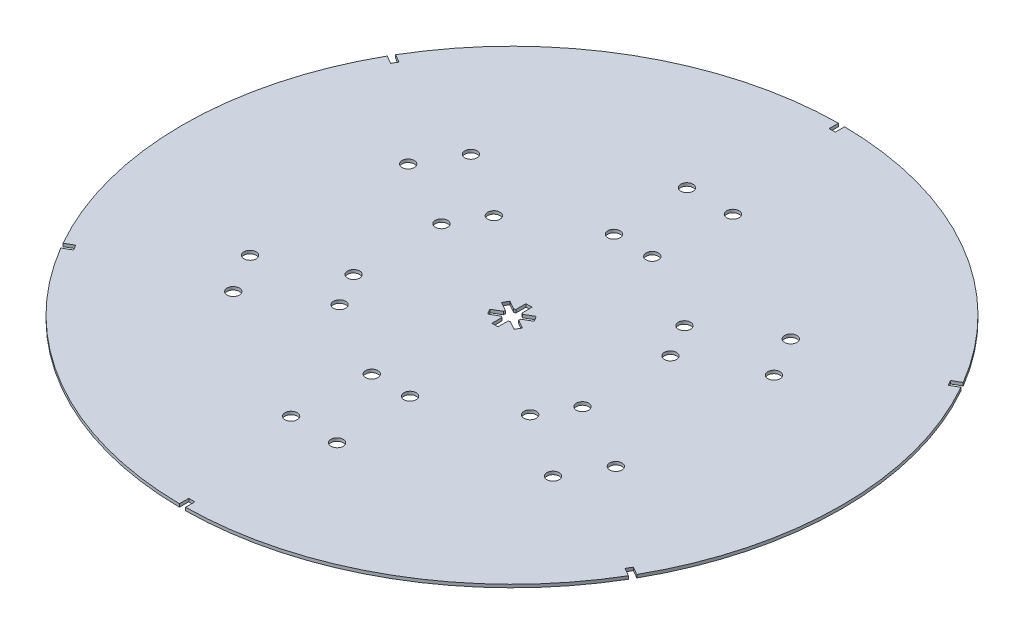
SolidWorks part; units mm, degrees
ref_plane "Front Plane" through (0, 0, 0) normal (0, 0, 1) x (1, 0, 0)
ref_plane "Top Plane" through (0, 0, 0) normal (0, 1, 0) x (1, 0, 0)
ref_plane "Right Plane" through (0, 0, 0) normal (1, 0, 0) x (0, 0, -1)
sketch "Sketch1" plane through (0, 0, 0) normal (0, 1, 0) x (1, 0, 0)
  line L0 (0, -1000) -> (0, 49000) construction
  line L1 (-1000, 0) -> (49000, 0) construction
  line L2 (0, 0) -> (-234.4645, 135.3681) construction
  line L3 (0, 0) -> (234.4645, 135.3681) construction
  line L4 (0, 0) -> (-234.4645, -135.3681) construction
  line L5 (0, 0) -> (234.4645, -135.3681) construction
  line L6 (-187.1874, 105.7633) -> (-181.9214, 102.723)
  line L7 (-181.9214, 102.723) -> (-179.9214, 106.1871)
  line L8 (-185.1874, 109.2274) -> (-179.9214, 106.1871)
  line L9 (-2, 214.9907) -> (-2, 208.9101)
  line L10 (2, 214.9907) -> (2, 208.9101)
  line L11 (-2, 208.9101) -> (2, 208.9101)
  line L12 (185.1874, 109.2274) -> (179.9214, 106.1871)
  line L13 (187.1874, 105.7633) -> (181.9214, 102.723)
  line L14 (179.9214, 106.1871) -> (181.9214, 102.723)
  line L15 (187.1874, -105.7633) -> (181.9214, -102.723)
  line L16 (185.1874, -109.2274) -> (179.9214, -106.1871)
  line L17 (181.9214, -102.723) -> (179.9214, -106.1871)
  line L18 (2, -214.9907) -> (2, -208.9101)
  line L19 (-2, -214.9907) -> (-2, -208.9101)
  line L20 (2, -208.9101) -> (-2, -208.9101)
  line L21 (-185.1874, -109.2274) -> (-179.9214, -106.1871)
  line L22 (-187.1874, -105.7633) -> (-181.9214, -102.723)
  line L23 (-179.9214, -106.1871) -> (-181.9214, -102.723)
  line L24 (-8.6093, 7.2903) -> (-2.9608, 4.0291)
  line L25 (-10.6093, 3.8262) -> (-4.9608, 0.565)
  line L27 (-10.6093, 3.8262) -> (-8.6093, 7.2903)
  line L28 (2.0089, 11.101) -> (2.0089, 4.5787)
  line L29 (-1.9911, 11.101) -> (2.0089, 11.101)
  line L30 (-1.9911, 11.101) -> (-1.9911, 4.5787)
  line L31 (10.6182, 3.8107) -> (4.9697, 0.5495)
  line L32 (8.6182, 7.2748) -> (10.6182, 3.8107)
  line L33 (8.6182, 7.2748) -> (2.9697, 4.0137)
  line L34 (8.6093, -7.2903) -> (2.9608, -4.0291)
  line L35 (10.6093, -3.8262) -> (8.6093, -7.2903)
  line L36 (10.6093, -3.8262) -> (4.9608, -0.565)
  line L37 (-2.0089, -11.101) -> (-2.0089, -4.5787)
  line L38 (1.9911, -11.101) -> (-2.0089, -11.101)
  line L39 (1.9911, -11.101) -> (1.9911, -4.5787)
  line L40 (-10.6182, -3.8107) -> (-4.9697, -0.5495)
  line L41 (-8.6182, -7.2748) -> (-10.6182, -3.8107)
  line L42 (-8.6182, -7.2748) -> (-2.9697, -4.0137)
  line L43 (0, 0) -> (-16.2703, 28.181) construction
  line L44 (0, 0) -> (74.6811, 28.6834) construction
  line L45 (0, 0) -> (-12.5, -79.0174) construction
  arc A0 (-187.1874, 105.7633) -> (-187.1874, -105.7633) centre (0, 0) ccw
  circle A1 centre (0, 0) radius 80 construction
  circle A2 centre (0, 0) radius 130 construction
  arc A3 (-4.9675, 0.5689) -> (-4.9697, -0.5495) centre (0, 0) ccw
  circle A4 centre (-119.3313, -51.5755) radius 4
  circle A5 centre (-104.3313, -77.5562) radius 4
  circle A6 centre (-74.6811, -28.6834) radius 4
  circle A7 centre (-62.1811, -50.334) radius 4
  circle A8 centre (-119.3313, 51.5755) radius 4
  circle A9 centre (-104.3313, 77.5562) radius 4
  circle A10 centre (-15, 129.1317) radius 4
  circle A11 centre (15, 129.1317) radius 4
  circle A12 centre (104.3313, 77.5562) radius 4
  circle A13 centre (119.3313, 51.5755) radius 4
  circle A14 centre (119.3313, -51.5755) radius 4
  circle A15 centre (104.3313, -77.5562) radius 4
  circle A16 centre (15, -129.1317) radius 4
  circle A17 centre (-15, -129.1317) radius 4
  circle A18 centre (-15, 129.1317) radius 4
  circle A19 centre (15, 129.1317) radius 4
  circle A20 centre (12.5, 79.0174) radius 4
  circle A21 centre (-12.5, 79.0174) radius 4
  circle A22 centre (119.3313, -51.5755) radius 4
  circle A23 centre (104.3313, -77.5562) radius 4
  circle A24 centre (62.1811, -50.334) radius 4
  circle A25 centre (74.6811, -28.6834) radius 4
  arc A26 (-2, 214.9907) -> (-185.1874, 109.2274) centre (0, 0) ccw
  arc A27 (185.1874, 109.2274) -> (2, 214.9907) centre (0, 0) ccw
  arc A28 (187.1874, -105.7633) -> (187.1874, 105.7633) centre (0, 0) ccw
  arc A29 (2, -214.9907) -> (185.1874, -109.2274) centre (0, 0) ccw
  arc A30 (-186.1955, -107.5) -> (-2, -214.9907) centre (0, 0) ccw
  arc A31 (-2.9765, -4.0175) -> (-2.0089, -4.5787) centre (0, 0) ccw
  arc A32 (1.9911, -4.5865) -> (2.9608, -4.0291) centre (0, 0) ccw
  arc A33 (4.9675, -0.5689) -> (4.9697, 0.5495) centre (0, 0) ccw
  arc A34 (2.9765, 4.0175) -> (2.0089, 4.5787) centre (0, 0) ccw
  arc A35 (-1.9911, 4.5865) -> (-2.9608, 4.0291) centre (0, 0) ccw
  circle A36 centre (62.1811, 50.334) radius 4
  circle A37 centre (74.6811, 28.6834) radius 4
  circle A38 centre (12.5, -79.0174) radius 4
  circle A39 centre (-12.5, -79.0174) radius 4
  circle A40 centre (-74.6811, 28.6834) radius 4
  circle A41 centre (-62.1811, 50.334) radius 4
  point P44 (0, 0)
  point P62 (0, 0)
  point P64 (-180.9214, 104.455)
  point P87 (0, 0)
  point P90 (-4.3301, 2.5)
  point P114 (0, 0)
  dimension "D1" = 430
  dimension "D2" = 10
  dimension "D3" = 160
  dimension "D4" = 260
  dimension "D5" = 30
  dimension "D7" = 8
  dimension "D8" = 25
  dimension "D9" = 8
  dimension "D6" = 30
  dimension "D10" = 6
  dimension "D12" = 2
  dimension "D13" = 2
  dimension "D16" = 60
  dimension "D18" = 120
  dimension "D11" = 3
  dimension "D14" = 6
  dimension "D15" = 6
  dimension "D17" = 3
extrude "Boss-Extrude1" add sketch "Sketch1" along normal mid plane 2 contours L21 A30 L19 L20 L18 A29 L16 L17 L15 A28 L13 L14 L12 A27 L10 L11 L9 A26 L8 L7 L6 A0 L22 L23 A35 L30 L29 L28 A34 L33 L32 L31 A33 L36 L35 L34 A32 L39 L38 L37 A31 L42 L41 L40 A3 L25 L27 L24 A4
